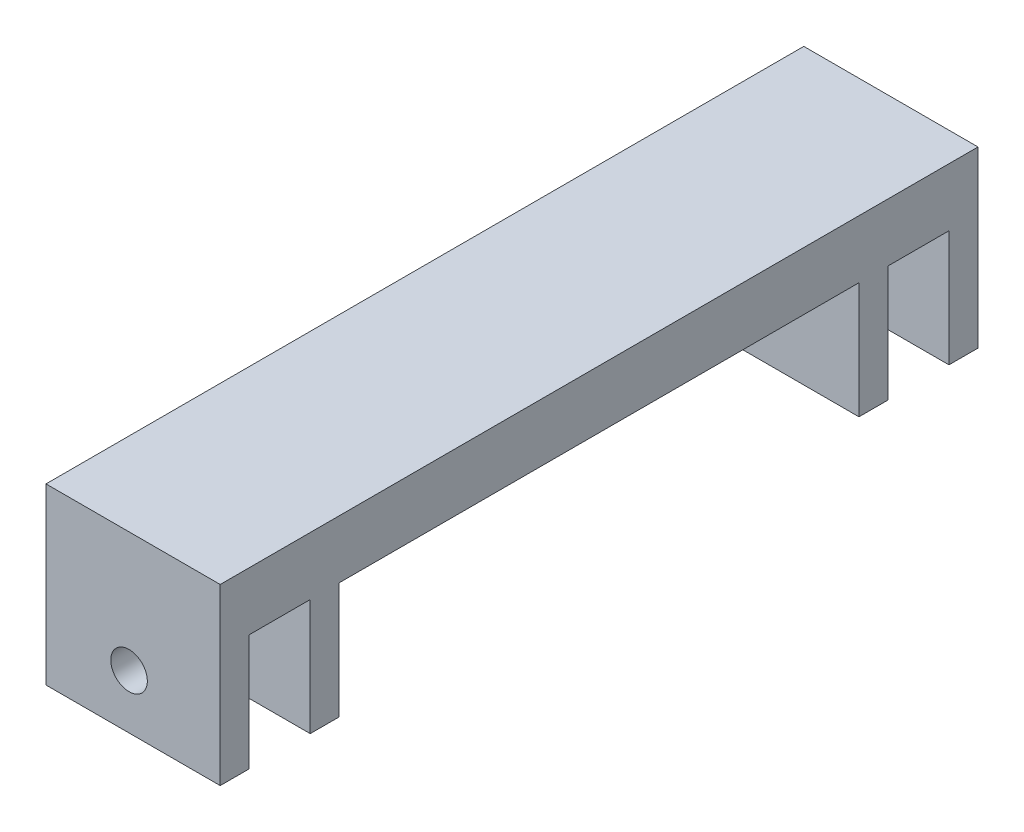
SolidWorks part; units mm, degrees
ref_plane "Plan de face" through (0, 0, 0) normal (0, 0, 1) x (1, 0, 0)
ref_plane "Plan de dessus" through (0, 0, 0) normal (0, 1, 0) x (1, 0, 0)
ref_plane "Plan de droite" through (0, 0, 0) normal (1, 0, 0) x (0, 0, -1)
sketch "Esquisse1" plane through (0, 0, 0) normal (0, 0, 1) x (1, 0, 0)
  line L1 (0, 0) -> (30, 0)
  line L2 (0, 0) -> (0, 10)
  line L3 (0, 10) -> (30, 10)
  line L4 (30, 0) -> (30, 10)
  dimension "D1" = 30
  dimension "D2" = 10
extrude "Boss.-Extru.1" add sketch "Esquisse1" along normal blind 130.5
sketch "Esquisse2" plane through (0, 0, 0) normal (0, -1, 0) x (1, 0, 0)
  line L0 (30, 130.5) -> (30, 0) construction
  line L1 (0, 0) -> (30, 0)
  line L2 (0, 0) -> (0, 5)
  line L3 (0, 5) -> (30, 5)
  line L4 (30, 0) -> (30, 5)
  line L5 (0, 130.5) -> (0, 0) construction
  line L6 (30, 15.5) -> (0, 15.5)
  line L7 (30, 15.5) -> (30, 20.5)
  line L8 (30, 20.5) -> (0, 20.5)
  line L9 (0, 15.5) -> (0, 20.5)
  line L11 (0, 130.5) -> (30, 130.5)
  line L12 (0, 130.5) -> (0, 125.5)
  line L13 (0, 125.5) -> (30, 125.5)
  line L14 (30, 130.5) -> (30, 125.5)
  line L15 (30, 115) -> (0, 115)
  line L16 (30, 115) -> (30, 110)
  line L17 (30, 110) -> (0, 110)
  line L18 (0, 115) -> (0, 110)
  dimension "D1" = 5
  dimension "D2" = 5
  dimension "D3" = 5
  dimension "D4" = 5
  dimension "D5" = 10.5
  dimension "D6" = 10.5
extrude "Boss.-Extru.2" add sketch "Esquisse2" along normal blind 20
sketch "Esquisse3" plane through (0, 0, 130.5) normal (0, 0, 1) x (1, 0, 0)
  line L0 (30, -20) -> (0, -20) construction
  line L1 (30, -20) -> (30, 10) construction
  circle A0 centre (14.3021, -10.6869) radius 3.15
  point P2 (14.3021, -10.6869)
  point P4 (15.0181, -10.4033)
  dimension "D1" = 6.3
  dimension "D2" = 9.3131
  dimension "D3" = 15.6979
extrude "Enlèv. mat.-Extru.2" cut sketch "Esquisse3" against normal through all
